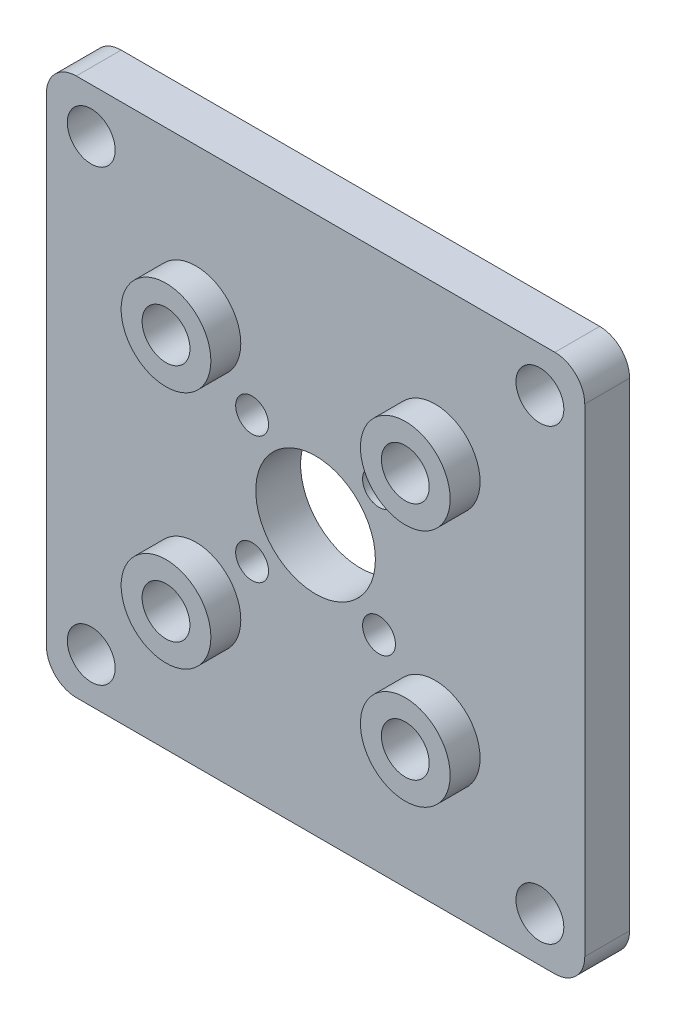
SolidWorks part; units mm, degrees
ref_plane "Plan de face" through (0, 0, 0) normal (0, 0, 1) x (1, 0, 0)
ref_plane "Plan de dessus" through (0, 0, 0) normal (0, 1, 0) x (1, 0, 0)
ref_plane "Plan de droite" through (0, 0, 0) normal (1, 0, 0) x (0, 0, -1)
sketch "Esquisse1" plane through (0, 0, 0) normal (0, 0, 1) x (1, 0, 0)
  line L0 (0, 6) -> (0, 0) construction
  line L1 (0, 0) -> (-4.2426, 4.2426) construction
  line L2 (0, 18) -> (0, 0) construction
  line L3 (18, -18) -> (-18, -18)
  line L4 (18, -18) -> (18, 18)
  line L5 (18, 18) -> (-18, 18)
  line L6 (-18, -18) -> (-18, 18)
  line L7 (18, -18) -> (-18, 18) construction
  line L8 (18, 18) -> (-18, -18) construction
  line L9 (0, 0) -> (18, 0) construction
  circle A0 centre (0, 0) radius 6 construction
  circle A1 centre (-4.2426, 4.2426) radius 1.1
  circle A2 centre (4.2426, 4.2426) radius 1.1
  circle A3 centre (4.2426, -4.2426) radius 1.1
  circle A4 centre (-4.2426, -4.2426) radius 1.1
  circle A5 centre (0, 0) radius 4
  circle A6 centre (-15, 15) radius 1.6
  circle A7 centre (0, 0) radius 15 construction
  circle A8 centre (15, 15) radius 1.6
  circle A9 centre (15, -15) radius 1.6
  circle A10 centre (-15, -15) radius 1.6
  point P14 (0, 0)
  dimension "D1" = 12
  dimension "D4" = 2.2
  dimension "D5" = 8
  dimension "D9" = 3.2
  dimension "D10" = 30
  dimension "D2" = 45
  dimension "D6" = 36
  dimension "D7" = 3
  dimension "D8" = 3
  dimension "D3" = 4
extrude "Boss.-Extru.1" add sketch "Esquisse1" along normal blind 3
sketch "Esquisse2" plane through (0, 0, 3) normal (0, 0, 1) x (1, 0, 0)
  line L1 (8, -8) -> (-8, -8) construction
  line L2 (8, -8) -> (8, 8) construction
  line L3 (8, 8) -> (-8, 8) construction
  line L4 (-8, -8) -> (-8, 8) construction
  line L5 (8, -8) -> (-8, 8) construction
  line L6 (8, 8) -> (-8, -8) construction
  circle A0 centre (-8, 8) radius 3
  circle A1 centre (8, 8) radius 3
  circle A2 centre (8, -8) radius 3
  circle A3 centre (-8, -8) radius 3
  point P0 (0, 0)
  dimension "D1" = 6
  dimension "D2" = 16
  dimension "D3" = 16
extrude "Boss.-Extru.2" add sketch "Esquisse2" along normal blind 2
sketch "Esquisse3" plane through (0, 0, 5) normal (0, 0, 1) x (1, 0, 0)
  line L0 (0, 17.8842) -> (0, 0) construction
  line L1 (0, 0) -> (17.8818, 0) construction
  circle A0 centre (-8, 8) radius 1.6
  circle A1 centre (-8, 8) radius 3 construction
  circle A2 centre (8, 8) radius 1.6
  circle A3 centre (8, -8) radius 1.6
  circle A4 centre (-8, -8) radius 1.6
  dimension "D1" = 3.2
extrude "Enlèv. mat.-Extru.1" cut sketch "Esquisse3" against normal through all
fillet "Congé1" radius 2 4 edges at (-18, 18, 1.5) (-18, -18, 1.5) (18, -18, 1.5) (18, 18, 1.5)
